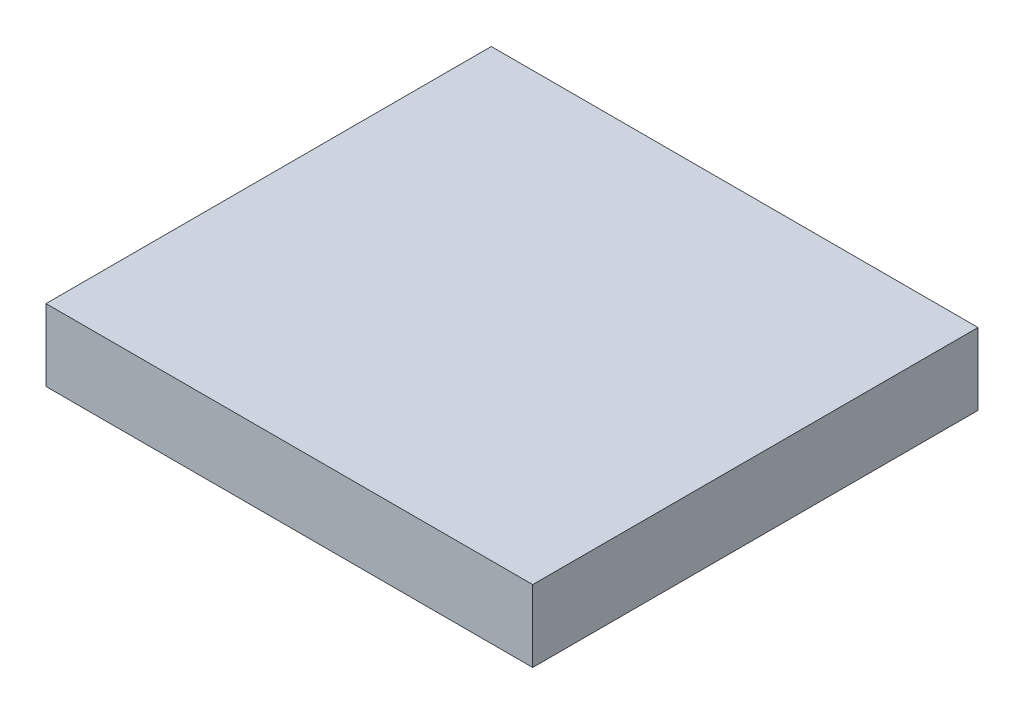
SolidWorks part; units mm, degrees
ref_plane "Front Plane" through (0, 0, 0) normal (0, 0, 1) x (1, 0, 0)
ref_plane "Top Plane" through (0, 0, 0) normal (0, 1, 0) x (1, 0, 0)
ref_plane "Right Plane" through (0, 0, 0) normal (1, 0, 0) x (0, 0, -1)
sketch "Sketch1" plane through (0, 0, 0) normal (0, 1, 0) x (1, 0, 0)
  line L1 (-33.8815, -31) -> (33.8815, -31)
  line L2 (-33.8815, -31) -> (-33.8815, 31)
  line L3 (-33.8815, 31) -> (33.8815, 31)
  line L4 (33.8815, -31) -> (33.8815, 31)
  line L5 (-33.8815, -31) -> (33.8815, 31) construction
  line L6 (-33.8815, 31) -> (33.8815, -31) construction
  point P0 (0, 0)
  dimension "D1" = 62
extrude "Boss-Extrude1" add sketch "Sketch1" along normal blind 10
